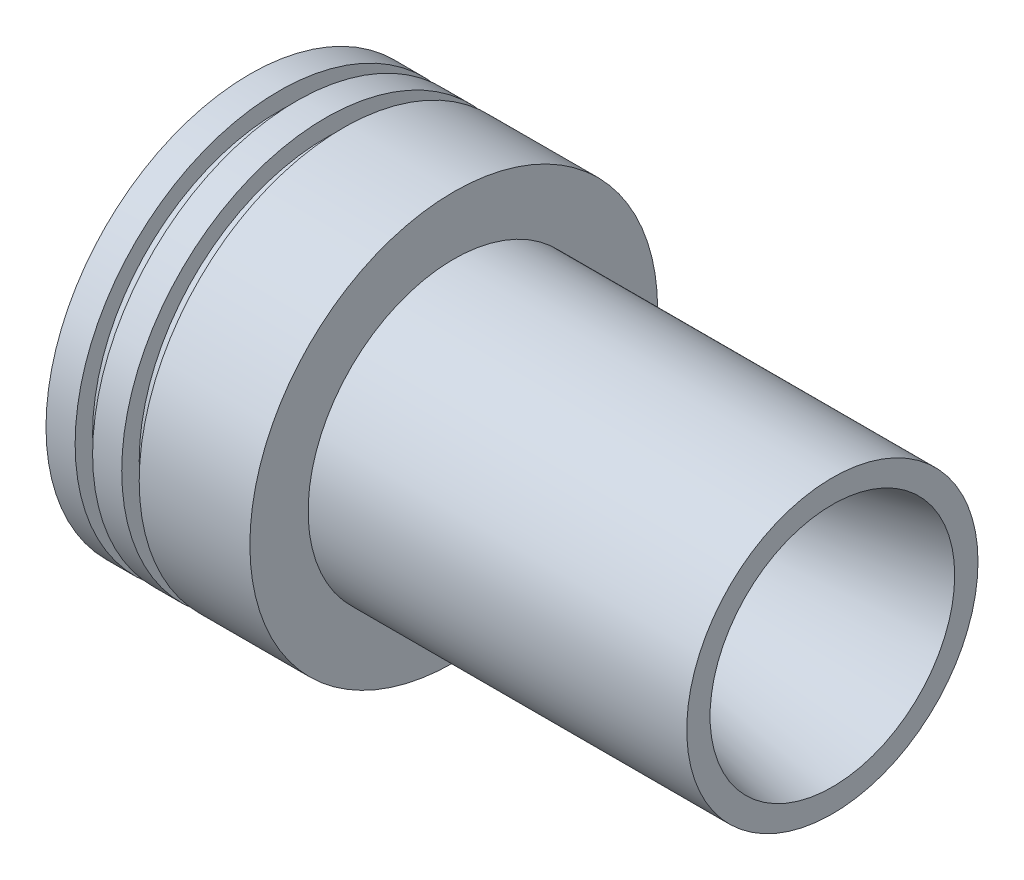
SolidWorks part; units mm, degrees
ref_plane "Front Plane" through (0, 0, 0) normal (0, 0, 1) x (1, 0, 0)
ref_plane "Top Plane" through (0, 0, 0) normal (0, 1, 0) x (1, 0, 0)
ref_plane "Right Plane" through (0, 0, 0) normal (1, 0, 0) x (0, 0, -1)
sketch "Sketch1" plane through (0, 0, 0) normal (1, 0, 0) x (0, 0, -1)
  circle A0 centre (0, 0) radius 35
  dimension "D1" = 70
extrude "Boss-Extrude1" add sketch "Sketch1" along normal blind 35
sketch "Sketch2" plane through (35, 0, 0) normal (1, 0, 0) x (0, 0, -1)
  circle A0 centre (0, 0) radius 25
  dimension "D1" = 50
extrude "Boss-Extrude2" add sketch "Sketch2" along normal blind 65
ref_plane "Plane1" through (30.8, 0, 0) normal (-1, 0, 0) x (0, 0, 1)
ref_plane "Plane2" through (31.8, 0, 0) normal (1, 0, 0) x (0, 0, -1)
ref_plane "Plane3" through (0, 0, 0) normal (-1, 0, 0) x (0, 0, 1)
ref_plane "Plane4" through (100, 0, 0) normal (1, 0, 0) x (0, 0, -1)
sketch "Sketch5" plane through (0, 0, 0) normal (-1, 0, 0) x (0, 0, 1)
  circle A0 centre (0, 0) radius 26
  dimension "D1" = 52
sketch "Sketch6" plane through (100, 0, 0) normal (1, 0, 0) x (0, 0, -1)
  circle A0 centre (0, 0) radius 21
  dimension "D1" = 42
sketch "Sketch7" plane through (30.8, 0, 0) normal (-1, 0, 0) x (0, 0, 1)
  circle A0 centre (0, 0) radius 6.5
loft "Cut-Loft1" cut profiles "Sketch5", "Sketch7"
sketch "Sketch8" plane through (31.8, 0, 0) normal (1, 0, 0) x (0, 0, -1)
  circle A0 centre (0, 0) radius 6.5
  dimension "D1" = 13
loft "Cut-Loft2" cut profiles "Sketch6", "Sketch8"
sketch "Sketch9" plane through (30.8, 0, 0) normal (-1, 0, 0) x (0, 0, 1)
  circle A0 centre (0, 0) radius 6.5
ref_plane "Plane5" through (0, 0, 0) normal (0, 0, 1) x (1, 0, 0)
sketch "Sketch12" plane through (0, 0, 0) normal (0, 0, 1) x (1, 0, 0)
  line L0 (0, 35) -> (5, 35)
  line L1 (0, 38.5) -> (0, -38.5) construction
  line L2 (35, 35) -> (0, 35) construction
  line L3 (5, 35) -> (5, 32)
  line L4 (5, 32) -> (8, 32)
  line L5 (8, 32) -> (8, 35)
  line L6 (8, 35) -> (13, 35)
  line L7 (13, 35) -> (13, 32)
  line L8 (13, 32) -> (16, 32)
  line L9 (16, 32) -> (16, 35)
  line L10 (16, 35) -> (16, 38.4555)
  line L11 (16, 38.4555) -> (0, 38.4555)
  line L12 (0, 38.4555) -> (0, 35)
  line L13 (0, 0) -> (102.6779, 0) construction
  line L14 (35, 0) -> (0, 0) construction
  dimension "D1" = 5
  dimension "D2" = 3
  dimension "D3" = 3
  dimension "D4" = 5
  dimension "D5" = 3
revolve "Cut-Revolve1" cut sketch "Sketch12" angle 360 about L13
sketch "Sketch13" plane through (0, 0, 0) normal (-1, 0, 0) x (0, 0, 1)
  circle A0 centre (0, 0) radius 6.5
extrude "Cut-Extrude2" cut sketch "Sketch13" against normal blind 100
